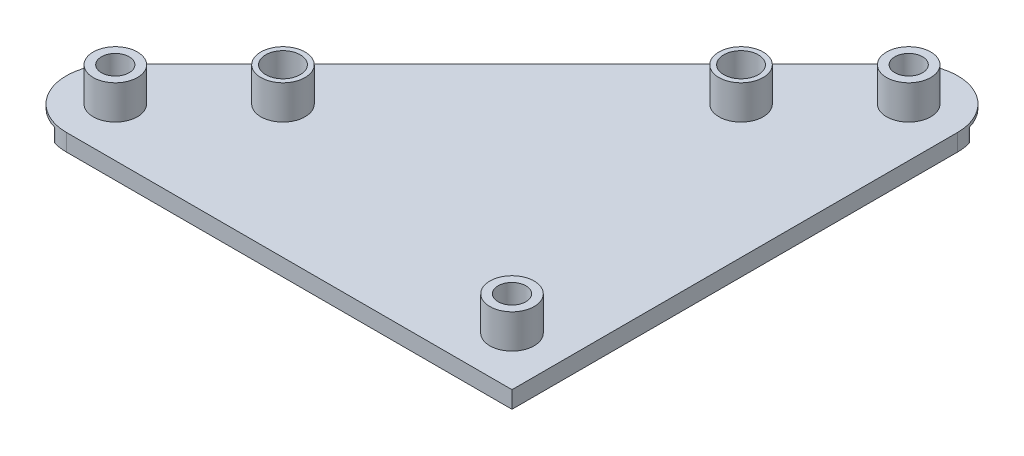
SolidWorks part; units mm, degrees
ref_plane "Front Plane" through (0, 0, 0) normal (0, 0, 1) x (1, 0, 0)
ref_plane "Top Plane" through (0, 0, 0) normal (0, 1, 0) x (1, 0, 0)
ref_plane "Right Plane" through (0, 0, 0) normal (1, 0, 0) x (0, 0, -1)
sketch "Sketch1" plane through (0, 0, 0) normal (0, 1, 0) x (1, 0, 0)
  line L5 (0, 0) -> (-91.9078, 24.6266) construction
  line L6 (-91.9078, 24.6266) -> (-24.6266, 91.9078)
  line L8 (14.4, -14.4) -> (14.4, 116.5345)
  line L11 (14.4, -14.4) -> (-116.5345, -14.4)
  line L15 (-116.5345, 0) -> (0, 116.5345) construction
  line L18 (-126.7168, 10.1823) -> (-10.1823, 126.7168)
  line L19 (-24.6266, 91.9078) -> (0, 0) construction
  line L22 (-116.5345, 0) -> (0, 0) construction
  line L24 (0, 116.5345) -> (0, 0) construction
  circle A5 centre (-116.5345, 0) radius 4.075
  circle A6 centre (0, 116.5345) radius 4.075
  arc A8 (-116.5345, -14.4) -> (-126.7168, 10.1823) centre (-116.5345, 0) cw
  arc A9 (14.4, 116.5345) -> (-10.1823, 126.7168) centre (0, 116.5345) ccw
  circle A11 centre (0, 0) radius 4.075
  circle A12 centre (-91.9078, 24.6266) radius 5.075
  circle A13 centre (-24.6266, 91.9078) radius 5.075
  point P0 (0, 0)
  point P12 (-130.6644, 2.7756)
  point P14 (-103.8056, 86.1926)
  dimension "D2" = 95.15
  dimension "D4" = 8.15
  dimension "D5" = 95.15
  dimension "D6" = 10.15
  dimension "D3" = 8.15
  dimension "D7" = 164.8046
  dimension "D1" = 14.4
extrude "Boss-Extrude1" add sketch "Sketch1" along normal blind 1
sketch "Sketch3" plane through (0, 0, 0) normal (0, -1, 0) x (1, 0, 0)
  line L0 (12.4, 12.4) -> (12.4, -123.8557)
  line L1 (12.4, 12.4) -> (-123.8557, 12.4)
  line L2 (12.4, 12.4) -> (12.4, 14.4) construction
  line L3 (12.4, 12.4) -> (14.4, 12.4) construction
  line L4 (14.4, -116.5345) -> (14.4, 14.4)
  line L6 (-126.7168, -10.1823) -> (-10.1823, -126.7168)
  line L7 (14.4, -116.5345) -> (14.4, 14.4)
  line L12 (14.4, 14.4) -> (-116.5345, 14.4) construction
  line L13 (14.4, 14.4) -> (14.4, -116.5345) construction
  line L16 (14.4, 14.4) -> (-116.5345, 14.4)
  line L17 (14.4, 14.4) -> (-116.5345, 14.4)
  arc A3 (-116.5345, 14.4) -> (-126.7168, -10.1823) centre (-116.5345, 0) ccw
  arc A5 (-10.1823, -126.7168) -> (14.4, -116.5345) centre (0, -116.5345) ccw
  arc A6 (-116.5345, 14.4) -> (-123.8557, 12.4) centre (-116.5345, 0) ccw
  arc A8 (12.4, -123.8557) -> (14.4, -116.5345) centre (0, -116.5345) ccw
  point P0 (13.4, 11.4)
  dimension "D1" = 0
  dimension "D2" = 2
extrude "Boss-Extrude3" add sketch "Sketch3" along normal blind 4
fillet "Fillet2" radius 0.75 2 edges at (-123.8557, -2, 12.4) (12.4, -2, -123.8557)
sketch "Sketch4" plane through (0, 1, 0) normal (0, 1, 0) x (1, 0, 0)
  circle A1 centre (-116.5345, 0) radius 4.075 construction
  circle A2 centre (0, 116.5345) radius 4.075 construction
  circle A4 centre (-116.5345, 0) radius 4.075
  circle A5 centre (0, 116.5345) radius 4.075
  circle A7 centre (-116.5345, 0) radius 6.5
  circle A8 centre (0, 116.5345) radius 6.5
  circle A9 centre (-24.6266, 91.9078) radius 5.075 construction
  circle A10 centre (-91.9078, 24.6266) radius 5.075 construction
  circle A11 centre (0, 0) radius 4.075 construction
  circle A12 centre (-24.6266, 91.9078) radius 5.075
  circle A13 centre (-91.9078, 24.6266) radius 5.075
  circle A14 centre (0, 0) radius 4.075
  circle A15 centre (-91.9078, 24.6266) radius 6.5
  circle A16 centre (-24.6266, 91.9078) radius 6.5
  circle A18 centre (0, 0) radius 6.5
  dimension "D1" = 13
extrude "Boss-Extrude4" add sketch "Sketch4" along normal blind 10
